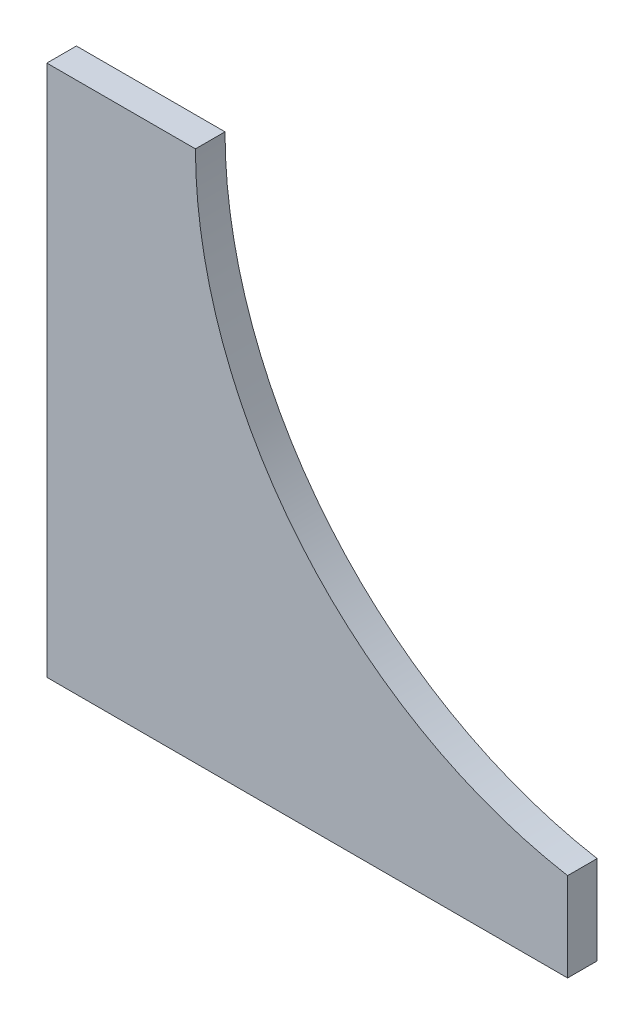
SolidWorks part; units mm, degrees
ref_plane "Alzado" through (0, 0, 0) normal (0, 0, 1) x (1, 0, 0)
ref_plane "Planta" through (0, 0, 0) normal (0, 1, 0) x (1, 0, 0)
ref_plane "Vista lateral" through (0, 0, 0) normal (1, 0, 0) x (0, 0, -1)
sketch "Croquis1" plane through (0, 0, 0) normal (0, 0, 1) x (1, 0, 0)
  line L0 (-56.2877, 206.1475) -> (-56.2877, 26.1475)
  line L1 (-56.2877, 26.1475) -> (119.9186, 26.1475)
  line L2 (-56.2877, 206.1475) -> (-6.0032, 206.1475)
  line L3 (119.9186, 26.1475) -> (119.9186, 56.1475)
  arc A0 (-6.0032, 206.1475) -> (119.9186, 56.1475) centre (146.2989, 206.1475) ccw
extrude "Saliente-Extruir1" add sketch "Croquis1" along normal blind 10
